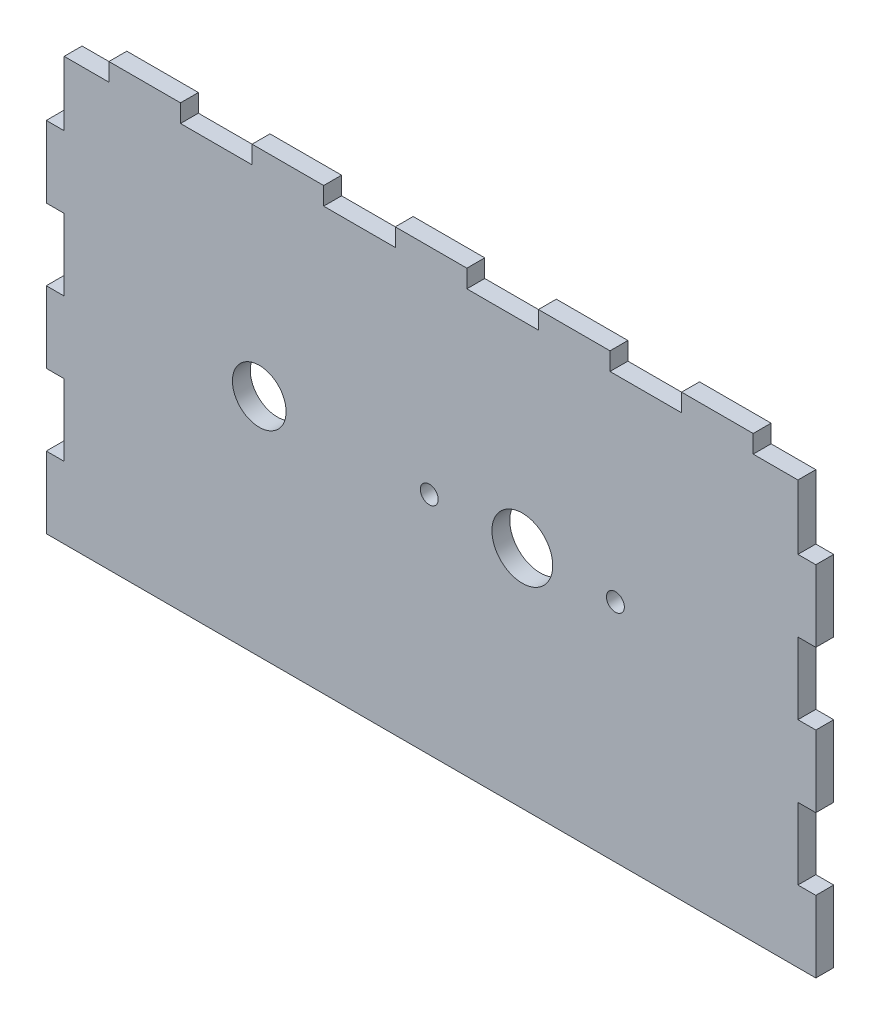
SolidWorks part; units mm, degrees
ref_plane "정면" through (0, 0, 0) normal (0, 0, 1) x (1, 0, 0)
ref_plane "윗면" through (0, 0, 0) normal (0, 1, 0) x (1, 0, 0)
ref_plane "우측면" through (0, 0, 0) normal (1, 0, 0) x (0, 0, -1)
sketch "스케치1" plane through (0, 0, 0) normal (0, 0, 1) x (1, 0, 0)
  line L0 (25.5, 64.0818) -> (25.5, -68.5321) construction
  line L1 (-102.5, 59) -> (102.5, 59)
  line L2 (-102.5, 59) -> (-102.5, -59)
  line L3 (-102.5, -59) -> (102.5, -59)
  line L4 (102.5, 59) -> (102.5, -59)
  line L5 (-102.5, 59) -> (102.5, -59) construction
  line L6 (-102.5, -59) -> (102.5, 59) construction
  circle A0 centre (25.5, 4) radius 8.5
  circle A1 centre (-48, 4) radius 7.5
  circle A5 centre (-0.5, 4) radius 2.5
  circle A7 centre (51.5, 4) radius 2.5
  point P0 (0, 0)
  dimension "D3" = 15
  dimension "D8" = 5
  dimension "D9" = 52
  dimension "D10" = 17
  dimension "D1" = 205
  dimension "D2" = 118
  dimension "D4" = 54.5
  dimension "D5" = 55
  dimension "D6" = 73.5
  dimension "D7" = 55
extrude "보스-돌출1" add sketch "스케치1" along normal blind 5 contours L4 L1 L2 L3 A0 A1 A5 A7
sketch "스케치2" plane through (0, 0, 5) normal (0, 0, 1) x (1, 0, 0)
  line L5 (102.5, -59) -> (107.5, -59)
  line L6 (102.5, -59) -> (102.5, -39)
  line L7 (102.5, -39) -> (107.5, -39)
  line L8 (107.5, -59) -> (107.5, -39)
  dimension "D1" = 5
  dimension "D2" = 20
extrude "보스-돌출2" add sketch "스케치2" against normal up to surface (5 mm away) contours L7 L8 L5 L6 up to face at (0, 0, 0)
pattern_linear "선형 패턴2" count 3 spacing 40 along (0, 1, 0) of "보스-돌출2"
mirror "대칭 복사2" about plane through (0, 0, 0) normal (1, 0, 0) of "선형 패턴2", "보스-돌출2"
sketch "스케치3" plane through (0, 0, 5) normal (0, 0, 1) x (1, 0, 0)
  line L0 (-102.5, 59) -> (102.5, 59) construction
  line L1 (10, 59) -> (-10, 59)
  line L2 (10, 59) -> (10, 64)
  line L3 (10, 64) -> (-10, 64)
  line L4 (-10, 59) -> (-10, 64)
  line L5 (0, 199.5713) -> (0, -71.5713) construction
  point P9 (0, 64)
  dimension "D1" = 5
  dimension "D2" = 20
extrude "보스-돌출3" add sketch "스케치3" against normal up to surface (5 mm away) up to face at (0, 0.8333, 0)
pattern_linear "선형 패턴3" count 3 spacing 40 along (1, 0, 0) of "보스-돌출3"
pattern_linear "선형 패턴4" count 3 spacing 40 along (-1, 0, 0) of "보스-돌출3"
